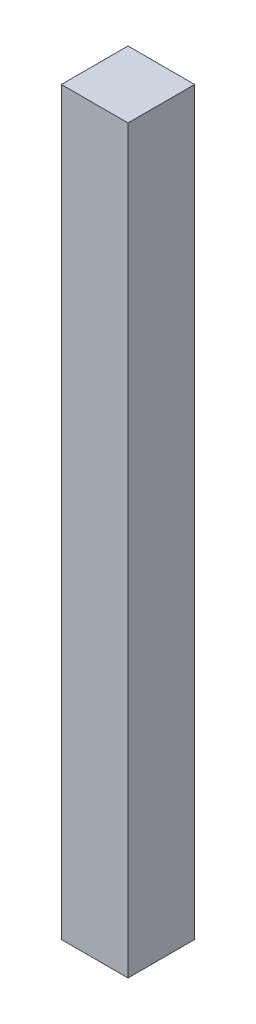
SolidWorks part; units mm, degrees
ref_plane "Front Plane" through (0, 0, 0) normal (0, 0, 1) x (1, 0, 0)
ref_plane "Top Plane" through (0, 0, 0) normal (0, 1, 0) x (1, 0, 0)
ref_plane "Right Plane" through (0, 0, 0) normal (1, 0, 0) x (0, 0, -1)
other "Configuration Table"
sketch "Sketch1" plane through (0, 0, 0) normal (0, 0, 1) x (1, 0, 0)
  line L1 (637, 770) -> (655, 770)
  line L2 (637, 770) -> (637, 970)
  line L3 (637, 970) -> (655, 970)
  line L4 (655, 770) -> (655, 970)
extrude "TOPPING_klape_kat3_gazli_amortisor_2_1" add sketch "Sketch1" along normal blind 18 from offset 8 separate body
